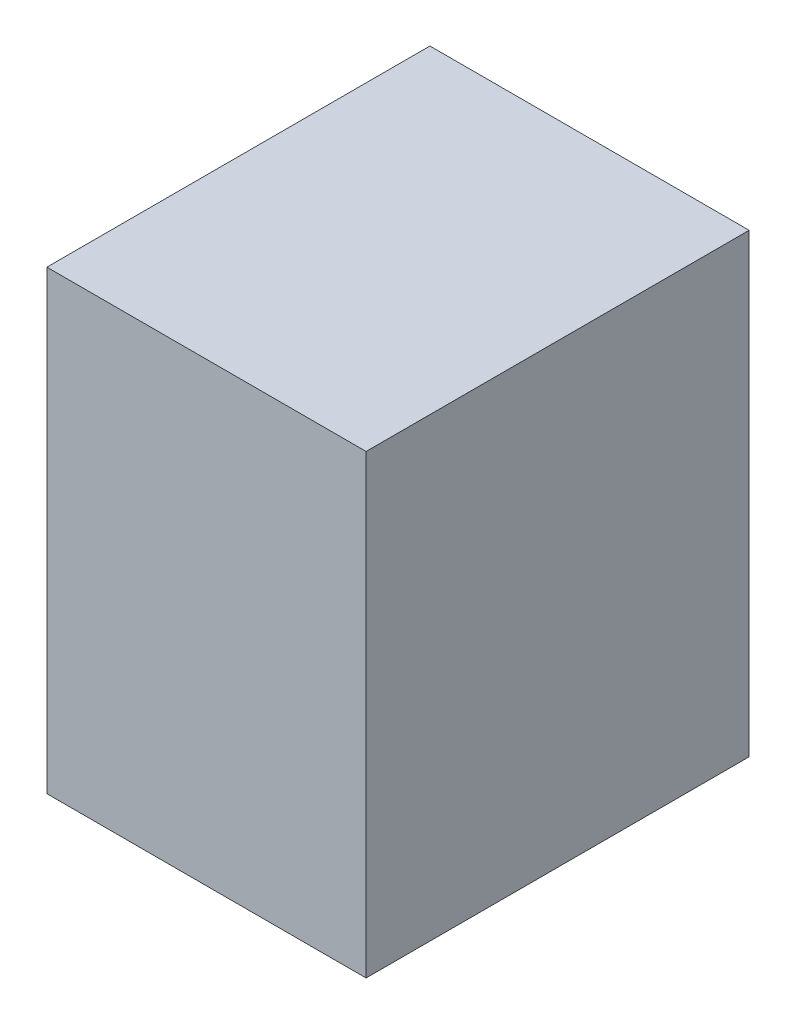
SolidWorks part; units mm, degrees
ref_plane "Front Plane" through (0, 0, 0) normal (0, 0, 1) x (1, 0, 0)
ref_plane "Top Plane" through (0, 0, 0) normal (0, 1, 0) x (1, 0, 0)
ref_plane "Right Plane" through (0, 0, 0) normal (1, 0, 0) x (0, 0, -1)
sketch "Sketch1" plane through (0, 0, 0) normal (0, 1, 0) x (1, 0, 0)
  line L1 (-8.75, -10.5) -> (8.75, -10.5)
  line L2 (-8.75, -10.5) -> (-8.75, 10.5)
  line L3 (-8.75, 10.5) -> (8.75, 10.5)
  line L4 (8.75, -10.5) -> (8.75, 10.5)
  line L5 (-8.75, -10.5) -> (8.75, 10.5) construction
  line L6 (-8.75, 10.5) -> (8.75, -10.5) construction
  point P0 (0, 0)
  dimension "D1" = 17.5
  dimension "D2" = 21
extrude "Boss-Extrude1" add sketch "Sketch1" along normal blind 25
